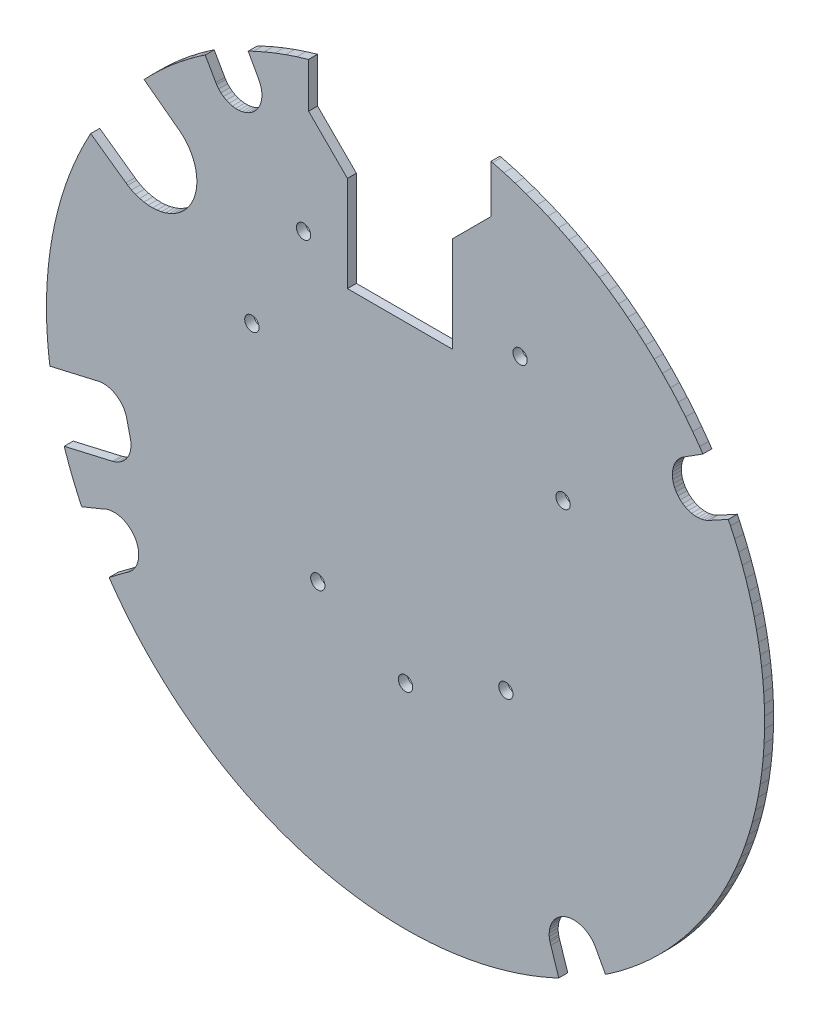
SolidWorks part; units mm, degrees
ref_plane "Płaszczyzna przednia" through (0, 0, 0) normal (0, 0, 1) x (1, 0, 0)
ref_plane "Płaszczyzna górna" through (0, 0, 0) normal (0, 1, 0) x (1, 0, 0)
ref_plane "Płaszczyzna prawa" through (0, 0, 0) normal (1, 0, 0) x (0, 0, -1)
sketch "Model" plane through (0, 0, 0) normal (0, 0, 1) x (1, 0, 0)
  line L0 (19.0436, 77.7128) -> (19.4019, 77.6294)
  line L1 (19.0436, 77.7128) -> (19.0437, 67.0537)
  line L2 (10.4176, 58.4277) -> (19.0437, 67.0537)
  line L3 (10.4176, 37.1511) -> (10.4176, 58.4277)
  line L4 (-12.9504, 37.1511) -> (10.4176, 37.1511)
  line L5 (-12.9504, 58.4177) -> (-12.9504, 37.1511)
  line L6 (-12.9603, 58.4177) -> (-12.9504, 58.4177)
  line L7 (-21.5964, 67.0537) -> (-12.9603, 58.4177)
  line L8 (-21.5964, 77.0457) -> (-21.5964, 67.0537)
  line L9 (-21.7211, 77.0127) -> (-21.5964, 77.0457)
  line L10 (-24.2112, 76.2665) -> (-21.7211, 77.0127)
  line L11 (-26.6758, 75.4398) -> (-24.2112, 76.2665)
  line L12 (-29.1122, 74.5335) -> (-26.6758, 75.4398)
  line L13 (-31.5179, 73.5485) -> (-29.1122, 74.5335)
  line L14 (-33.8903, 72.4859) -> (-31.5179, 73.5485)
  line L15 (-35.0587, 71.9164) -> (-33.8903, 72.4859)
  line L16 (-35.0587, 71.9164) -> (-32.6893, 67.604)
  line L17 (-32.6893, 67.604) -> (-32.532, 67.296)
  line L18 (-32.532, 67.296) -> (-32.2769, 66.6533)
  line L19 (-32.2769, 66.6533) -> (-32.1045, 65.9836)
  line L20 (-32.1045, 65.9836) -> (-32.0176, 65.2976)
  line L21 (-32.0176, 65.2976) -> (-32.0067, 64.9519)
  line L22 (-32.0185, 64.5922) -> (-32.0067, 64.9519)
  line L23 (-32.1126, 63.8788) -> (-32.0185, 64.5922)
  line L24 (-32.2991, 63.1839) -> (-32.1126, 63.8788)
  line L25 (-32.5747, 62.5193) -> (-32.2991, 63.1839)
  line L26 (-32.9349, 61.8965) -> (-32.5747, 62.5193)
  line L27 (-33.3734, 61.3261) -> (-32.9349, 61.8965)
  line L28 (-33.8827, 60.8178) -> (-33.3734, 61.3261)
  line L29 (-34.4541, 60.3805) -> (-33.8827, 60.8178)
  line L30 (-35.0777, 60.0216) -> (-34.4541, 60.3805)
  line L31 (-35.7428, 59.7473) -> (-35.0777, 60.0216)
  line L32 (-36.4381, 59.5623) -> (-35.7428, 59.7473)
  line L33 (-37.1516, 59.4698) -> (-36.4381, 59.5623)
  line L34 (-37.8711, 59.4713) -> (-37.1516, 59.4698)
  line L35 (-38.5843, 59.5668) -> (-37.8711, 59.4713)
  line L36 (-39.2788, 59.7547) -> (-38.5843, 59.5668)
  line L37 (-39.9428, 60.0317) -> (-39.2788, 59.7547)
  line L38 (-40.5649, 60.3932) -> (-39.9428, 60.0317)
  line L39 (-41.1344, 60.8328) -> (-40.5649, 60.3932)
  line L40 (-41.6416, 61.3432) -> (-41.1344, 60.8328)
  line L41 (-42.0777, 61.9154) -> (-41.6416, 61.3432)
  line L42 (-42.2668, 62.2217) -> (-42.0777, 61.9154)
  line L43 (-44.6488, 66.3807) -> (-42.2668, 62.2217)
  line L44 (-45.8412, 65.5873) -> (-44.6488, 66.3807)
  line L45 (-48.1485, 63.9127) -> (-45.8412, 65.5873)
  line L46 (-50.3947, 62.1569) -> (-48.1485, 63.9127)
  line L47 (-52.5769, 60.3223) -> (-50.3947, 62.1569)
  line L48 (-54.6923, 58.4111) -> (-52.5769, 60.3223)
  line L49 (-56.7384, 56.4257) -> (-54.6923, 58.4111)
  line L50 (-58.2639, 54.8361) -> (-56.7384, 56.4257)
  line L51 (-58.2639, 54.8361) -> (-50.5268, 49.0454)
  line L52 (-50.5268, 49.0454) -> (-50.1364, 48.7535)
  line L53 (-50.1364, 48.7535) -> (-49.416, 48.0964)
  line L54 (-49.416, 48.0964) -> (-48.7629, 47.3723)
  line L55 (-48.7629, 47.3723) -> (-48.1833, 46.5882)
  line L56 (-48.1833, 46.5882) -> (-47.6828, 45.7514)
  line L57 (-47.6828, 45.7514) -> (-47.2661, 44.8699)
  line L58 (-47.2661, 44.8699) -> (-46.937, 43.952)
  line L59 (-46.937, 43.952) -> (-46.6989, 43.0065)
  line L60 (-46.6989, 43.0065) -> (-46.5538, 42.0423)
  line L61 (-46.5538, 42.0423) -> (-46.5032, 41.0685)
  line L62 (-46.5476, 40.0945) -> (-46.5032, 41.0685)
  line L63 (-46.6865, 39.1294) -> (-46.5476, 40.0945)
  line L64 (-46.9186, 38.1823) -> (-46.6865, 39.1294)
  line L65 (-47.2418, 37.2624) -> (-46.9186, 38.1823)
  line L66 (-47.6529, 36.3782) -> (-47.2418, 37.2624)
  line L67 (-48.148, 35.5383) -> (-47.6529, 36.3782)
  line L68 (-48.7226, 34.7504) -> (-48.148, 35.5383)
  line L69 (-49.371, 34.0222) -> (-48.7226, 34.7504)
  line L70 (-50.0872, 33.3606) -> (-49.371, 34.0222)
  line L71 (-50.8644, 32.7717) -> (-50.0872, 33.3606)
  line L72 (-51.6951, 32.2612) -> (-50.8644, 32.7717)
  line L73 (-52.5716, 31.834) -> (-51.6951, 32.2612)
  line L74 (-53.4855, 31.494) -> (-52.5716, 31.834)
  line L75 (-54.4281, 31.2446) -> (-53.4855, 31.494)
  line L76 (-55.3905, 31.088) -> (-54.4281, 31.2446)
  line L77 (-56.3636, 31.0258) -> (-55.3905, 31.088)
  line L78 (-57.3381, 31.0586) -> (-56.3636, 31.0258)
  line L79 (-58.3048, 31.1859) -> (-57.3381, 31.0586)
  line L80 (-59.2545, 31.4068) -> (-58.3048, 31.1859)
  line L81 (-60.1783, 31.7189) -> (-59.2545, 31.4068)
  line L82 (-61.0673, 32.1195) -> (-60.1783, 31.7189)
  line L83 (-61.9131, 32.6046) -> (-61.0673, 32.1195)
  line L84 (-62.3104, 32.8871) -> (-61.9131, 32.6046)
  line L85 (-70.16, 38.4692) -> (-62.3104, 32.8871)
  line L86 (-70.3157, 38.1943) -> (-70.16, 38.4692)
  line L87 (-71.6317, 35.6653) -> (-70.3157, 38.1943)
  line L88 (-72.8567, 33.0909) -> (-71.6317, 35.6653)
  line L89 (-73.9893, 30.4746) -> (-72.8567, 33.0909)
  line L90 (-75.0279, 27.8195) -> (-73.9893, 30.4746)
  line L91 (-75.9713, 25.1292) -> (-75.0279, 27.8195)
  line L92 (-76.8182, 22.4069) -> (-75.9713, 25.1292)
  line L93 (-77.5677, 19.6563) -> (-76.8182, 22.4069)
  line L94 (-78.2186, 16.8806) -> (-77.5677, 19.6563)
  line L95 (-78.7703, 14.0836) -> (-78.2186, 16.8806)
  line L96 (-79.222, 11.2686) -> (-78.7703, 14.0836)
  line L97 (-79.5731, 8.4394) -> (-79.222, 11.2686)
  line L98 (-79.8233, 5.5994) -> (-79.5731, 8.4394)
  line L99 (-79.9721, 2.7524) -> (-79.8233, 5.5994)
  line L100 (-80.0194, -0.0982) -> (-79.9721, 2.7524)
  line L101 (-80.0194, -0.0982) -> (-79.9651, -2.9486)
  line L102 (-79.9651, -2.9486) -> (-79.8093, -5.7953)
  line L103 (-79.8093, -5.7953) -> (-79.5522, -8.6347)
  line L104 (-79.5522, -8.6347) -> (-79.256, -10.9739)
  line L105 (-79.256, -10.9739) -> (-68.5352, -8.4988)
  line L106 (-68.5352, -8.4988) -> (-68.1939, -8.42)
  line L107 (-68.1939, -8.42) -> (-67.4966, -8.3528)
  line L108 (-67.4966, -8.3528) -> (-66.7965, -8.3773)
  line L109 (-66.7965, -8.3773) -> (-66.1056, -8.4929)
  line L110 (-66.1056, -8.4929) -> (-65.4357, -8.6977)
  line L111 (-65.4357, -8.6977) -> (-64.7982, -8.9882)
  line L112 (-64.7982, -8.9882) -> (-64.2042, -9.3594)
  line L113 (-64.2042, -9.3594) -> (-63.6636, -9.805)
  line L114 (-63.6636, -9.805) -> (-63.1859, -10.3174)
  line L115 (-63.1859, -10.3174) -> (-62.7791, -10.8877)
  line L116 (-62.7791, -10.8877) -> (-62.4502, -11.5062)
  line L117 (-62.4502, -11.5062) -> (-62.2049, -12.1624)
  line L118 (-62.2049, -12.1624) -> (-62.1261, -12.5037)
  line L119 (-62.1261, -12.5037) -> (-61.3306, -15.949)
  line L120 (-61.3306, -15.949) -> (-61.2518, -16.2903)
  line L121 (-61.2518, -16.2903) -> (-61.1847, -16.9876)
  line L122 (-61.2092, -17.6877) -> (-61.1847, -16.9876)
  line L123 (-61.3248, -18.3787) -> (-61.2092, -17.6877)
  line L124 (-61.5296, -19.0486) -> (-61.3248, -18.3787)
  line L125 (-61.8201, -19.686) -> (-61.5296, -19.0486)
  line L126 (-62.1913, -20.2801) -> (-61.8201, -19.686)
  line L127 (-62.6369, -20.8206) -> (-62.1913, -20.2801)
  line L128 (-63.1492, -21.2984) -> (-62.6369, -20.8206)
  line L129 (-63.7196, -21.7052) -> (-63.1492, -21.2984)
  line L130 (-64.3381, -22.0341) -> (-63.7196, -21.7052)
  line L131 (-64.9942, -22.2794) -> (-64.3381, -22.0341)
  line L132 (-65.3355, -22.3582) -> (-64.9942, -22.2794)
  line L133 (-76.0604, -24.8342) -> (-65.3355, -22.3582)
  line L134 (-76.0604, -24.8342) -> (-75.9094, -25.3156)
  line L135 (-75.9094, -25.3156) -> (-74.9594, -28.0036)
  line L136 (-74.9594, -28.0036) -> (-73.9142, -30.6561)
  line L137 (-73.9142, -30.6561) -> (-72.7753, -33.2696)
  line L138 (-72.7753, -33.2696) -> (-72.1596, -34.5553)
  line L139 (-72.1596, -34.5553) -> (-67.6684, -32.7253)
  line L140 (-67.6684, -32.7253) -> (-67.3503, -32.558)
  line L141 (-67.3503, -32.558) -> (-66.6869, -32.2879)
  line L142 (-66.6869, -32.2879) -> (-65.9939, -32.1065)
  line L143 (-65.9939, -32.1065) -> (-65.2832, -32.0167)
  line L144 (-65.2832, -32.0167) -> (-64.5669, -32.0202)
  line L145 (-64.5669, -32.0202) -> (-63.8572, -32.1169)
  line L146 (-63.8572, -32.1169) -> (-63.166, -32.3051)
  line L147 (-63.166, -32.3051) -> (-62.5052, -32.5817)
  line L148 (-62.5052, -32.5817) -> (-61.886, -32.9419)
  line L149 (-61.886, -32.9419) -> (-61.319, -33.3796)
  line L150 (-61.319, -33.3796) -> (-60.8137, -33.8873)
  line L151 (-60.8137, -33.8873) -> (-60.3788, -34.4565)
  line L152 (-60.3788, -34.4565) -> (-60.0217, -35.0774)
  line L153 (-60.0217, -35.0774) -> (-59.7484, -35.7396)
  line L154 (-59.7484, -35.7396) -> (-59.5635, -36.4316)
  line L155 (-59.5635, -36.4316) -> (-59.4703, -37.1418)
  line L156 (-59.4703, -37.1418) -> (-59.4586, -37.5)
  line L157 (-59.4706, -37.8617) -> (-59.4586, -37.5)
  line L158 (-59.5656, -38.5787) -> (-59.4706, -37.8617)
  line L159 (-59.754, -39.277) -> (-59.5656, -38.5787)
  line L160 (-60.0325, -39.9445) -> (-59.754, -39.277)
  line L161 (-60.3964, -40.5697) -> (-60.0325, -39.9445)
  line L162 (-60.8392, -41.1416) -> (-60.3964, -40.5697)
  line L163 (-61.3533, -41.6504) -> (-60.8392, -41.1416)
  line L164 (-61.9297, -42.0872) -> (-61.3533, -41.6504)
  line L165 (-62.2383, -42.2762) -> (-61.9297, -42.0872)
  line L166 (-66.0586, -45.1369) -> (-62.2383, -42.2762)
  line L167 (-66.0586, -45.1369) -> (-65.2616, -46.3033)
  line L168 (-65.2616, -46.3033) -> (-63.5863, -48.5783)
  line L169 (-63.5863, -48.5783) -> (-61.8318, -50.7928)
  line L170 (-61.8318, -50.7928) -> (-60.0001, -52.9439)
  line L171 (-60.0001, -52.9439) -> (-58.0936, -55.0291)
  line L172 (-58.0936, -55.0291) -> (-56.1148, -57.0456)
  line L173 (-56.1148, -57.0456) -> (-54.0659, -58.9911)
  line L174 (-54.0659, -58.9911) -> (-51.9497, -60.863)
  line L175 (-51.9497, -60.863) -> (-49.7687, -62.659)
  line L176 (-49.7687, -62.659) -> (-47.5256, -64.3769)
  line L177 (-47.5256, -64.3769) -> (-45.2234, -66.0146)
  line L178 (-45.2234, -66.0146) -> (-42.8647, -67.5699)
  line L179 (-42.8647, -67.5699) -> (-40.4526, -69.041)
  line L180 (-40.4526, -69.041) -> (-37.99, -70.4261)
  line L181 (-37.99, -70.4261) -> (-35.4801, -71.7233)
  line L182 (-35.4801, -71.7233) -> (-32.926, -72.9311)
  line L183 (-32.926, -72.9311) -> (-30.3308, -74.0481)
  line L184 (-30.3308, -74.0481) -> (-27.6978, -75.0727)
  line L185 (-27.6978, -75.0727) -> (-25.0303, -76.0037)
  line L186 (-25.0303, -76.0037) -> (-22.3316, -76.8399)
  line L187 (-22.3316, -76.8399) -> (-19.605, -77.5804)
  line L188 (-19.605, -77.5804) -> (-16.854, -78.2241)
  line L189 (-16.854, -78.2241) -> (-14.082, -78.7704)
  line L190 (-14.082, -78.7704) -> (-11.2924, -79.2184)
  line L191 (-11.2924, -79.2184) -> (-8.4887, -79.5677)
  line L192 (-8.4887, -79.5677) -> (-5.6745, -79.8177)
  line L193 (-5.6745, -79.8177) -> (-2.8532, -79.9683)
  line L194 (-2.8532, -79.9683) -> (-0.0283, -80.0192)
  line L195 (-0.0283, -80.0192) -> (2.7966, -79.9703)
  line L196 (2.7966, -79.9703) -> (5.618, -79.8217)
  line L197 (5.618, -79.8217) -> (8.4324, -79.5737)
  line L198 (8.4324, -79.5737) -> (11.2363, -79.2264)
  line L199 (11.2363, -79.2264) -> (14.0262, -78.7803)
  line L200 (14.0262, -78.7803) -> (16.7986, -78.2361)
  line L201 (16.7986, -78.2361) -> (19.55, -77.5943)
  line L202 (19.55, -77.5943) -> (22.2771, -76.8557)
  line L203 (22.2771, -76.8557) -> (24.9765, -76.0214)
  line L204 (24.9765, -76.0214) -> (27.6446, -75.0923)
  line L205 (27.6446, -75.0923) -> (30.2784, -74.0695)
  line L206 (30.2784, -74.0695) -> (32.8743, -72.9544)
  line L207 (32.8743, -72.9544) -> (34.1518, -72.3514)
  line L208 (32.3764, -66.933) -> (34.1518, -72.3514)
  line L209 (32.2006, -66.3985) -> (32.3764, -66.933)
  line L210 (32.1226, -66.0744) -> (32.2006, -66.3985)
  line L211 (32.0263, -65.415) -> (32.1226, -66.0744)
  line L212 (32.0105, -64.7488) -> (32.0263, -65.415)
  line L213 (32.0105, -64.7488) -> (32.0755, -64.0856)
  line L214 (32.0755, -64.0856) -> (32.2203, -63.4352)
  line L215 (32.2203, -63.4352) -> (32.4428, -62.8071)
  line L216 (32.4428, -62.8071) -> (32.7397, -62.2105)
  line L217 (32.7397, -62.2105) -> (33.1067, -61.6543)
  line L218 (33.1067, -61.6543) -> (33.5383, -61.1466)
  line L219 (33.5383, -61.1466) -> (34.0282, -60.6949)
  line L220 (34.0282, -60.6949) -> (34.5692, -60.3059)
  line L221 (34.5692, -60.3059) -> (35.1534, -59.9852)
  line L222 (35.1534, -59.9852) -> (35.772, -59.7376)
  line L223 (35.772, -59.7376) -> (36.4161, -59.5667)
  line L224 (36.4161, -59.5667) -> (37.0762, -59.4751)
  line L225 (37.0762, -59.4751) -> (37.7424, -59.4641)
  line L226 (37.7424, -59.4641) -> (38.4052, -59.5338)
  line L227 (38.4052, -59.5338) -> (39.0545, -59.6833)
  line L228 (39.0545, -59.6833) -> (39.6811, -59.9102)
  line L229 (39.6811, -59.9102) -> (40.2755, -60.2114)
  line L230 (40.2755, -60.2114) -> (40.8291, -60.5824)
  line L231 (40.8291, -60.5824) -> (41.3337, -61.0176)
  line L232 (41.3337, -61.0176) -> (41.7818, -61.5107)
  line L233 (41.7818, -61.5107) -> (42.167, -62.0545)
  line L234 (42.167, -62.0545) -> (42.3342, -62.3429)
  line L235 (42.3342, -62.3429) -> (44.5493, -66.4474)
  line L236 (44.5493, -66.4474) -> (45.7221, -65.6698)
  line L237 (45.7221, -65.6698) -> (47.9923, -64.0295)
  line L238 (47.9923, -64.0295) -> (50.2037, -62.3107)
  line L239 (50.2037, -62.3107) -> (52.3536, -60.5156)
  line L240 (52.3536, -60.5156) -> (54.4394, -58.6463)
  line L241 (54.4394, -58.6463) -> (56.4584, -56.7052)
  line L242 (56.4584, -56.7052) -> (58.4083, -54.6947)
  line L243 (58.4083, -54.6947) -> (60.2867, -52.6171)
  line L244 (60.2867, -52.6171) -> (62.0911, -50.475)
  line L245 (62.0911, -50.475) -> (63.8195, -48.2711)
  line L246 (63.8195, -48.2711) -> (65.4698, -46.0081)
  line L247 (65.4698, -46.0081) -> (67.0398, -43.6887)
  line L248 (67.0398, -43.6887) -> (68.5277, -41.3158)
  line L249 (68.5277, -41.3158) -> (69.9316, -38.8923)
  line L250 (69.9316, -38.8923) -> (71.2498, -36.4211)
  line L251 (71.2498, -36.4211) -> (72.4808, -33.9053)
  line L252 (72.4808, -33.9053) -> (73.623, -31.348)
  line L253 (73.623, -31.348) -> (74.6749, -28.7523)
  line L254 (74.6749, -28.7523) -> (75.6354, -26.1213)
  line L255 (75.6354, -26.1213) -> (76.5032, -23.4583)
  line L256 (76.5032, -23.4583) -> (77.2773, -20.7666)
  line L257 (77.2773, -20.7666) -> (77.9567, -18.0495)
  line L258 (77.9567, -18.0495) -> (78.5407, -15.3102)
  line L259 (78.5407, -15.3102) -> (79.0283, -12.5522)
  line L260 (79.0283, -12.5522) -> (79.4192, -9.7788)
  line L261 (79.4192, -9.7788) -> (79.7128, -6.9934)
  line L262 (79.7128, -6.9934) -> (79.9087, -4.1995)
  line L263 (79.9087, -4.1995) -> (80.0067, -1.4004)
  line L264 (80.0067, 0) -> (80.0067, -1.4004)
  line L265 (80.0067, 0) -> (80.0067, 1.1336)
  line L266 (79.9425, 3.4) -> (80.0067, 1.1336)
  line L267 (79.8141, 5.6637) -> (79.9425, 3.4)
  line L268 (79.6215, 7.9228) -> (79.8141, 5.6637)
  line L269 (79.3651, 10.1755) -> (79.6215, 7.9228)
  line L270 (79.0449, 12.4201) -> (79.3651, 10.1755)
  line L271 (78.6613, 14.6547) -> (79.0449, 12.4201)
  line L272 (78.2145, 16.8775) -> (78.6613, 14.6547)
  line L273 (77.7049, 19.0868) -> (78.2145, 16.8775)
  line L274 (77.1329, 21.2808) -> (77.7049, 19.0868)
  line L275 (76.499, 23.4576) -> (77.1329, 21.2808)
  line L276 (75.8037, 25.6157) -> (76.499, 23.4576)
  line L277 (75.0475, 27.7531) -> (75.8037, 25.6157)
  line L278 (74.231, 29.8683) -> (75.0475, 27.7531)
  line L279 (73.355, 31.9595) -> (74.231, 29.8683)
  line L280 (72.42, 34.0251) -> (73.355, 31.9595)
  line L281 (71.9234, 35.0442) -> (72.42, 34.0251)
  line L282 (67.5882, 32.6807) -> (71.9234, 35.0442)
  line L283 (67.2673, 32.5185) -> (67.5882, 32.6807)
  line L284 (66.5971, 32.2589) -> (67.2673, 32.5185)
  line L285 (65.8987, 32.0889) -> (66.5971, 32.2589)
  line L286 (65.1841, 32.0116) -> (65.8987, 32.0889)
  line L287 (64.4655, 32.0283) -> (65.1841, 32.0116)
  line L288 (63.7552, 32.1387) -> (64.4655, 32.0283)
  line L289 (63.0655, 32.3408) -> (63.7552, 32.1387)
  line L290 (62.408, 32.6313) -> (63.0655, 32.3408)
  line L291 (61.7941, 33.0051) -> (62.408, 32.6313)
  line L292 (61.2342, 33.4559) -> (61.7941, 33.0051)
  line L293 (60.738, 33.9759) -> (61.2342, 33.4559)
  line L294 (60.314, 34.5563) -> (60.738, 33.9759)
  line L295 (59.9693, 35.187) -> (60.314, 34.5563)
  line L296 (59.71, 35.8574) -> (59.9693, 35.187)
  line L297 (59.5404, 36.5559) -> (59.71, 35.8574)
  line L298 (59.4634, 37.2705) -> (59.5404, 36.5559)
  line L299 (59.4634, 37.2705) -> (59.4804, 37.9891)
  line L300 (59.4804, 37.9891) -> (59.5911, 38.6993)
  line L301 (59.5911, 38.6993) -> (59.7936, 39.3889)
  line L302 (59.7936, 39.3889) -> (60.0844, 40.0463)
  line L303 (60.0844, 40.0463) -> (60.4585, 40.66)
  line L304 (60.4585, 40.66) -> (60.9096, 41.2196)
  line L305 (60.9096, 41.2196) -> (61.4299, 41.7156)
  line L306 (61.4299, 41.7156) -> (62.0104, 42.1394)
  line L307 (62.0104, 42.1394) -> (62.3202, 42.3219)
  line L308 (62.3202, 42.3219) -> (66.2604, 44.8277)
  line L309 (65.534, 45.9137) -> (66.2604, 44.8277)
  line L310 (64.008, 48.0182) -> (65.534, 45.9137)
  line L311 (62.4144, 50.072) -> (64.008, 48.0182)
  line L312 (60.755, 52.073) -> (62.4144, 50.072)
  line L313 (59.0315, 54.019) -> (60.755, 52.073)
  line L314 (57.2456, 55.908) -> (59.0315, 54.019)
  line L315 (55.3994, 57.738) -> (57.2456, 55.908)
  line L316 (53.4946, 59.5071) -> (55.3994, 57.738)
  line L317 (51.5334, 61.2133) -> (53.4946, 59.5071)
  line L318 (49.5179, 62.855) -> (51.5334, 61.2133)
  line L319 (47.45, 64.4303) -> (49.5179, 62.855)
  line L320 (45.3321, 65.9376) -> (47.45, 64.4303)
  line L321 (43.1663, 67.3753) -> (45.3321, 65.9376)
  line L322 (40.955, 68.7419) -> (43.1663, 67.3753)
  line L323 (38.7005, 70.036) -> (40.955, 68.7419)
  line L324 (36.4051, 71.2561) -> (38.7005, 70.036)
  line L325 (34.0713, 72.4011) -> (36.4051, 71.2561)
  line L326 (31.7015, 73.4696) -> (34.0713, 72.4011)
  line L327 (29.2983, 74.4606) -> (31.7015, 73.4696)
  line L328 (26.8641, 75.373) -> (29.2983, 74.4606)
  line L329 (24.4016, 76.2058) -> (26.8641, 75.373)
  line L330 (21.9133, 76.9582) -> (24.4016, 76.2058)
  line L331 (19.4019, 77.6294) -> (21.9133, 76.9582)
  circle A0 centre (54.7436, 37.2036) radius 0.55
  circle A1 centre (54.7437, 42.2836) radius 0.55
  circle A2 centre (54.7436, 39.7436) radius 0.55
  circle A3 centre (-42.5084, 0.296) radius 0.45
  circle A4 centre (-45.0484, 0.296) radius 0.45
  circle A5 centre (-43.7784, 0.296) radius 0.45
  circle A6 centre (-37.6913, 41.9936) radius 0.51
  circle A7 centre (-35.7314, 47.9937) radius 0.635
  circle A8 centre (-35.7314, 35.9936) radius 0.635
  circle A9 centre (-37.6913, 38.9937) radius 0.51
  circle A10 centre (-37.6913, 44.9936) radius 0.51
  circle A11 centre (-70.8843, 18.7637) radius 0.5
  circle A12 centre (-68.3443, 18.7637) radius 0.5
  circle A13 centre (-43.2714, 18.7886) radius 0.5
  circle A14 centre (-40.7314, 18.7886) radius 0.5
  circle A15 centre (-56.8443, 18.7637) radius 0.5
  circle A16 centre (-54.3043, 18.7637) radius 0.5
  circle A17 centre (-39.9663, -46.0063) radius 0.7
  circle A18 centre (-45.0464, -46.0063) radius 0.7
  circle A19 centre (-50.1264, -43.5063) radius 1.2
  circle A20 centre (-34.8863, -43.5063) radius 1.2
  circle A21 centre (-57.9123, -11.637) radius 0.0875
  circle A22 centre (-57.9998, -11.637) radius 0.0437
  circle A23 centre (-57.8248, -11.637) radius 0.0437
  circle A24 centre (-56.3123, -11.637) radius 0.0875
  circle A25 centre (-56.3998, -11.637) radius 0.0437
  circle A26 centre (-56.2248, -11.637) radius 0.0437
  circle A27 centre (-0.7564, -72.3564) radius 2.275
  circle A28 centre (-0.7564, -65.1563) radius 2.275
  circle A29 centre (72.7187, -2.7063) radius 2.275
  circle A30 centre (65.5186, -2.7063) radius 2.275
  circle A31 centre (9.9101, -35.1099) radius 0.45
  circle A32 centre (7.3701, -35.1099) radius 0.45
  circle A33 centre (8.6401, -35.1099) radius 0.45
  circle A34 centre (44.2637, 16.4937) radius 0.45
  circle A35 centre (41.7237, 16.4937) radius 0.45
  circle A36 centre (42.9937, 16.4937) radius 0.45
  circle A37 centre (47.9187, 12.5686) radius 0.0875
  circle A38 centre (47.8312, 12.5686) radius 0.0437
  circle A39 centre (48.0062, 12.5686) radius 0.0437
  circle A40 centre (49.5187, 12.5686) radius 0.0875
  circle A41 centre (49.4312, 12.5686) radius 0.0437
  circle A42 centre (49.6062, 12.5686) radius 0.0437
  circle A43 centre (34.9286, -38.2563) radius 0.51
  circle A44 centre (34.9286, -44.2563) radius 0.51
  circle A45 centre (32.9687, -47.2563) radius 0.635
  circle A46 centre (32.9687, -35.2563) radius 0.635
  circle A47 centre (34.9286, -41.2563) radius 0.51
  circle A48 centre (47.9937, 30.2437) radius 0.51
  circle A49 centre (47.9937, 42.2437) radius 0.51
  circle A50 centre (47.9937, 39.2437) radius 0.51
  circle A51 centre (47.9937, 45.2437) radius 0.51
  circle A52 centre (47.9937, 33.2436) radius 0.51
  circle A53 centre (47.9937, 36.2437) radius 0.51
  circle A54 centre (49.9537, 48.2437) radius 0.635
  circle A55 centre (49.9537, 27.2437) radius 0.635
  circle A56 centre (58.2437, 21.4937) radius 0.5
  circle A57 centre (63.3236, 21.4936) radius 0.5
  circle A58 centre (60.7837, 21.4936) radius 0.5
  circle A59 centre (65.8637, 21.4936) radius 0.5
  circle A60 centre (31.75, 3.048) radius 0.381
  circle A61 centre (31.75, 5.588) radius 0.381
  circle A62 centre (-11.5063, -69.7564) radius 0.4
  circle A63 centre (-11.5063, -64.7564) radius 0.4
  circle A64 centre (35.814, 15.494) radius 0.55
  circle A65 centre (35.814, 10.414) radius 0.55
  circle A66 centre (35.814, 12.954) radius 0.55
  circle A67 centre (35.814, 2.286) radius 0.55
  circle A68 centre (35.814, 4.826) radius 0.55
  circle A69 centre (35.814, 7.366) radius 0.55
  circle A70 centre (65.2436, -14.0063) radius 0.4
  circle A71 centre (60.2436, -14.0063) radius 0.4
  circle A72 centre (72.7436, 13.7437) radius 0.55
  circle A73 centre (72.7436, 11.2036) radius 0.55
  circle A74 centre (72.7436, 8.6636) radius 0.55
  circle A75 centre (26.801, 38.231) radius 0.381
  circle A76 centre (24.261, 38.231) radius 0.381
  circle A77 centre (21.086, 15.371) radius 0.381
  circle A78 centre (-21.459, 38.231) radius 0.381
  circle A79 centre (-23.999, 38.231) radius 0.381
  circle A80 centre (24.261, 25.531) radius 0.381
  circle A81 centre (25.531, 43.311) radius 1.5875
  circle A82 centre (-22.729, 43.311) radius 1.5875
  circle A83 centre (22.356, -22.729) radius 1.5875
  circle A84 centre (-19.554, -22.729) radius 1.5875
  circle A85 centre (-21.459, 35.691) radius 0.381
  circle A86 centre (-23.999, 35.691) radius 0.381
  circle A87 centre (-21.459, 33.151) radius 0.381
  circle A88 centre (-23.999, 33.151) radius 0.381
  circle A89 centre (-21.459, 28.071) radius 0.381
  circle A90 centre (-21.459, 25.531) radius 0.381
  circle A91 centre (-23.999, 25.531) radius 0.381
  circle A92 centre (-21.459, 22.991) radius 0.381
  circle A93 centre (-23.999, 22.991) radius 0.381
  circle A94 centre (-21.459, 20.451) radius 0.381
  circle A95 centre (-23.999, 20.451) radius 0.381
  circle A96 centre (-21.459, 17.911) radius 0.381
  circle A97 centre (-21.459, 15.371) radius 0.381
  circle A98 centre (-23.999, 15.371) radius 0.381
  circle A99 centre (-21.459, 12.831) radius 0.381
  circle A100 centre (-23.999, 12.831) radius 0.381
  circle A101 centre (-21.459, 10.291) radius 0.381
  circle A102 centre (-23.999, 10.291) radius 0.381
  circle A103 centre (-21.459, 7.751) radius 0.381
  circle A104 centre (-21.459, 5.211) radius 0.381
  circle A105 centre (-23.999, 5.211) radius 0.381
  circle A106 centre (-21.459, 2.671) radius 0.381
  circle A107 centre (-23.999, 2.671) radius 0.381
  circle A108 centre (-21.459, 0.131) radius 0.381
  circle A109 centre (-23.999, 0.131) radius 0.381
  circle A110 centre (-21.459, -2.409) radius 0.381
  circle A111 centre (-23.999, -2.409) radius 0.381
  circle A112 centre (-21.459, -4.949) radius 0.381
  circle A113 centre (-23.999, -4.949) radius 0.381
  circle A114 centre (-21.459, -7.489) radius 0.381
  circle A115 centre (-23.999, -7.489) radius 0.381
  circle A116 centre (-21.459, -10.029) radius 0.381
  circle A117 centre (-23.999, -10.029) radius 0.381
  circle A118 centre (-21.459, -12.569) radius 0.381
  circle A119 centre (-23.999, -12.569) radius 0.381
  circle A120 centre (-21.459, -15.109) radius 0.381
  circle A121 centre (-23.999, -15.109) radius 0.381
  circle A122 centre (-21.459, -17.649) radius 0.381
  circle A123 centre (-23.999, -17.649) radius 0.381
  circle A124 centre (26.801, 35.691) radius 0.381
  circle A125 centre (24.261, 35.691) radius 0.381
  circle A126 centre (24.261, 33.151) radius 0.381
  circle A127 centre (26.801, 30.611) radius 0.381
  circle A128 centre (24.261, 30.611) radius 0.381
  circle A129 centre (26.801, 28.071) radius 0.381
  circle A130 centre (24.261, 28.071) radius 0.381
  circle A131 centre (24.261, 22.991) radius 0.381
  circle A132 centre (26.801, 20.451) radius 0.381
  circle A133 centre (24.261, 20.451) radius 0.381
  circle A134 centre (26.801, 17.911) radius 0.381
  circle A135 centre (24.261, 17.911) radius 0.381
  circle A136 centre (26.801, 15.371) radius 0.381
  circle A137 centre (24.261, 15.371) radius 0.381
  circle A138 centre (26.801, 10.291) radius 0.381
  circle A139 centre (26.801, 7.751) radius 0.381
  circle A140 centre (26.801, 5.211) radius 0.381
  circle A141 centre (24.261, 5.211) radius 0.381
  circle A142 centre (26.801, 2.671) radius 0.381
  circle A143 centre (24.261, 2.671) radius 0.381
  circle A144 centre (26.801, 0.131) radius 0.381
  circle A145 centre (24.261, 0.131) radius 0.381
  circle A146 centre (26.801, -2.409) radius 0.381
  circle A147 centre (24.261, -2.409) radius 0.381
  circle A148 centre (26.801, -4.949) radius 0.381
  circle A149 centre (24.261, -4.949) radius 0.381
  circle A150 centre (26.801, -7.489) radius 0.381
  circle A151 centre (24.261, -7.489) radius 0.381
  circle A152 centre (26.801, -10.029) radius 0.381
  circle A153 centre (24.261, -10.029) radius 0.381
  circle A154 centre (26.801, -12.569) radius 0.381
  circle A155 centre (24.261, -12.569) radius 0.381
  circle A156 centre (26.801, -15.109) radius 0.381
  circle A157 centre (24.261, -15.109) radius 0.381
  circle A158 centre (26.801, -17.649) radius 0.381
  circle A159 centre (24.261, -17.649) radius 0.381
  circle A160 centre (21.086, 12.831) radius 0.381
  circle A161 centre (21.086, 10.291) radius 0.381
  circle A162 centre (21.086, 2.671) radius 0.381
  circle A163 centre (-23.999, 28.071) radius 0.381
  circle A164 centre (-23.999, 17.911) radius 0.381
  circle A165 centre (-21.459, 30.611) radius 0.381
  circle A166 centre (24.261, 7.751) radius 0.381
  circle A167 centre (26.801, 25.531) radius 0.381
  circle A168 centre (-23.999, 30.611) radius 0.381
  circle A169 centre (26.801, 22.991) radius 0.381
  circle A170 centre (24.261, 12.831) radius 0.381
  circle A171 centre (26.801, 12.831) radius 0.381
  circle A172 centre (26.801, 33.151) radius 0.381
  circle A173 centre (-23.999, 7.751) radius 0.381
  circle A174 centre (21.086, 7.751) radius 0.381
  circle A175 centre (21.086, 5.211) radius 0.381
  circle A176 centre (24.261, 10.291) radius 0.381
  circle A179 centre (19.0436, 77.7128) radius 0.25
  circle A182 centre (19.0437, 67.0537) radius 0.25
  circle A184 centre (10.4176, 58.4277) radius 0.25
  circle A186 centre (10.4176, 37.1511) radius 0.25
  circle A188 centre (-12.9504, 37.1511) radius 0.25
  circle A190 centre (-12.9504, 58.4177) radius 0.25
  circle A192 centre (-12.9603, 58.4177) radius 0.25
  circle A194 centre (-21.5964, 67.0537) radius 0.25
  circle A196 centre (-21.5964, 77.0457) radius 0.25
  circle A198 centre (-21.7211, 77.0127) radius 0.25
  circle A200 centre (-24.2112, 76.2665) radius 0.25
  circle A202 centre (-26.6758, 75.4398) radius 0.25
  circle A204 centre (-29.1122, 74.5335) radius 0.25
  circle A206 centre (-31.5179, 73.5485) radius 0.25
  circle A208 centre (-33.8903, 72.4859) radius 0.25
  circle A209 centre (-35.0587, 71.9164) radius 0.25
  circle A211 centre (-32.6893, 67.604) radius 0.25
  circle A213 centre (-32.532, 67.296) radius 0.25
  circle A215 centre (-32.2769, 66.6533) radius 0.25
  circle A217 centre (-32.1045, 65.9836) radius 0.25
  circle A219 centre (-32.0176, 65.2976) radius 0.25
  circle A222 centre (-32.0067, 64.9519) radius 0.25
  circle A224 centre (-32.0185, 64.5922) radius 0.25
  circle A226 centre (-32.1126, 63.8788) radius 0.25
  circle A228 centre (-32.2991, 63.1839) radius 0.25
  circle A230 centre (-32.5747, 62.5193) radius 0.25
  circle A232 centre (-32.9349, 61.8965) radius 0.25
  circle A234 centre (-33.3734, 61.3261) radius 0.25
  circle A236 centre (-33.8827, 60.8178) radius 0.25
  circle A238 centre (-34.4541, 60.3805) radius 0.25
  circle A240 centre (-35.0777, 60.0216) radius 0.25
  circle A242 centre (-35.7428, 59.7473) radius 0.25
  circle A244 centre (-36.4381, 59.5623) radius 0.25
  circle A246 centre (-37.1516, 59.4698) radius 0.25
  circle A248 centre (-37.8711, 59.4713) radius 0.25
  circle A250 centre (-38.5843, 59.5668) radius 0.25
  circle A252 centre (-39.2788, 59.7547) radius 0.25
  circle A254 centre (-39.9428, 60.0317) radius 0.25
  circle A256 centre (-40.5649, 60.3932) radius 0.25
  circle A258 centre (-41.1344, 60.8328) radius 0.25
  circle A260 centre (-41.6416, 61.3432) radius 0.25
  circle A262 centre (-42.0777, 61.9154) radius 0.25
  circle A264 centre (-42.2668, 62.2217) radius 0.25
  circle A266 centre (-44.6488, 66.3807) radius 0.25
  circle A268 centre (-45.8412, 65.5873) radius 0.25
  circle A270 centre (-48.1485, 63.9127) radius 0.25
  circle A272 centre (-50.3947, 62.1569) radius 0.25
  circle A274 centre (-52.5769, 60.3223) radius 0.25
  circle A276 centre (-54.6923, 58.4111) radius 0.25
  circle A278 centre (-56.7384, 56.4257) radius 0.25
  circle A279 centre (-58.2639, 54.8361) radius 0.25
  circle A281 centre (-50.5268, 49.0454) radius 0.25
  circle A283 centre (-50.1364, 48.7535) radius 0.25
  circle A285 centre (-49.416, 48.0964) radius 0.25
  circle A287 centre (-48.7629, 47.3723) radius 0.25
  circle A289 centre (-48.1833, 46.5882) radius 0.25
  circle A291 centre (-47.6828, 45.7514) radius 0.25
  circle A293 centre (-47.2661, 44.8699) radius 0.25
  circle A295 centre (-46.937, 43.952) radius 0.25
  circle A297 centre (-46.6989, 43.0065) radius 0.25
  circle A299 centre (-46.5538, 42.0423) radius 0.25
  circle A302 centre (-46.5032, 41.0685) radius 0.25
  circle A304 centre (-46.5476, 40.0945) radius 0.25
  circle A306 centre (-46.6865, 39.1294) radius 0.25
  circle A308 centre (-46.9186, 38.1823) radius 0.25
  circle A310 centre (-47.2418, 37.2624) radius 0.25
  circle A312 centre (-47.6529, 36.3782) radius 0.25
  circle A314 centre (-48.148, 35.5383) radius 0.25
  circle A316 centre (-48.7226, 34.7504) radius 0.25
  circle A318 centre (-49.371, 34.0222) radius 0.25
  circle A320 centre (-50.0872, 33.3606) radius 0.25
  circle A322 centre (-50.8644, 32.7717) radius 0.25
  circle A324 centre (-51.6951, 32.2612) radius 0.25
  circle A326 centre (-52.5716, 31.834) radius 0.25
  circle A328 centre (-53.4855, 31.494) radius 0.25
  circle A330 centre (-54.4281, 31.2446) radius 0.25
  circle A332 centre (-55.3905, 31.088) radius 0.25
  circle A334 centre (-56.3636, 31.0258) radius 0.25
  circle A336 centre (-57.3381, 31.0586) radius 0.25
  circle A338 centre (-58.3048, 31.1859) radius 0.25
  circle A340 centre (-59.2545, 31.4068) radius 0.25
  circle A342 centre (-60.1783, 31.7189) radius 0.25
  circle A344 centre (-61.0673, 32.1195) radius 0.25
  circle A346 centre (-61.9131, 32.6046) radius 0.25
  circle A350 centre (-62.3104, 32.8871) radius 0.25
  circle A352 centre (-70.16, 38.4692) radius 0.25
  circle A354 centre (-70.3157, 38.1943) radius 0.25
  circle A356 centre (-71.6317, 35.6653) radius 0.25
  circle A358 centre (-72.8567, 33.0909) radius 0.25
  circle A360 centre (-73.9893, 30.4746) radius 0.25
  circle A362 centre (-75.0279, 27.8195) radius 0.25
  circle A364 centre (-75.9713, 25.1292) radius 0.25
  circle A366 centre (-76.8182, 22.4069) radius 0.25
  circle A368 centre (-77.5677, 19.6563) radius 0.25
  circle A370 centre (-78.2186, 16.8806) radius 0.25
  circle A372 centre (-78.7703, 14.0836) radius 0.25
  circle A374 centre (-79.222, 11.2686) radius 0.25
  circle A376 centre (-79.5731, 8.4394) radius 0.25
  circle A378 centre (-79.8233, 5.5994) radius 0.25
  circle A380 centre (-79.9721, 2.7524) radius 0.25
  circle A381 centre (-80.0194, -0.0982) radius 0.25
  circle A383 centre (-79.9651, -2.9486) radius 0.25
  circle A385 centre (-79.8093, -5.7953) radius 0.25
  circle A387 centre (-79.5522, -8.6347) radius 0.25
  circle A389 centre (-79.256, -10.9739) radius 0.25
  circle A391 centre (-68.5352, -8.4988) radius 0.25
  circle A393 centre (-68.1939, -8.42) radius 0.25
  circle A395 centre (-67.4966, -8.3528) radius 0.25
  circle A397 centre (-66.7965, -8.3773) radius 0.25
  circle A399 centre (-66.1056, -8.4929) radius 0.25
  circle A401 centre (-65.4357, -8.6977) radius 0.25
  circle A403 centre (-64.7982, -8.9882) radius 0.25
  circle A405 centre (-64.2042, -9.3594) radius 0.25
  circle A407 centre (-63.6636, -9.805) radius 0.25
  circle A409 centre (-63.1859, -10.3174) radius 0.25
  circle A411 centre (-62.7791, -10.8877) radius 0.25
  circle A413 centre (-62.4502, -11.5062) radius 0.25
  circle A415 centre (-62.2049, -12.1624) radius 0.25
  circle A419 centre (-62.1261, -12.5037) radius 0.25
  circle A421 centre (-61.3306, -15.949) radius 0.25
  circle A423 centre (-61.2518, -16.2903) radius 0.25
  circle A426 centre (-61.1847, -16.9876) radius 0.25
  circle A428 centre (-61.2092, -17.6877) radius 0.25
  circle A430 centre (-61.3248, -18.3787) radius 0.25
  circle A432 centre (-61.5296, -19.0486) radius 0.25
  circle A434 centre (-61.8201, -19.686) radius 0.25
  circle A436 centre (-62.1913, -20.2801) radius 0.25
  circle A438 centre (-62.6369, -20.8206) radius 0.25
  circle A440 centre (-63.1492, -21.2984) radius 0.25
  circle A442 centre (-63.7196, -21.7052) radius 0.25
  circle A444 centre (-64.3381, -22.0341) radius 0.25
  circle A446 centre (-64.9942, -22.2794) radius 0.25
  circle A450 centre (-65.3355, -22.3582) radius 0.25
  circle A451 centre (-76.0604, -24.8342) radius 0.25
  circle A453 centre (-75.9094, -25.3156) radius 0.25
  circle A455 centre (-74.9594, -28.0036) radius 0.25
  circle A457 centre (-73.9142, -30.6561) radius 0.25
  circle A459 centre (-72.7753, -33.2696) radius 0.25
  circle A461 centre (-72.1596, -34.5553) radius 0.25
  circle A463 centre (-67.6684, -32.7253) radius 0.25
  circle A465 centre (-67.3503, -32.558) radius 0.25
  circle A467 centre (-66.6869, -32.2879) radius 0.25
  circle A469 centre (-65.9939, -32.1065) radius 0.25
  circle A471 centre (-65.2832, -32.0167) radius 0.25
  circle A473 centre (-64.5669, -32.0202) radius 0.25
  circle A475 centre (-63.8572, -32.1169) radius 0.25
  circle A477 centre (-63.166, -32.3051) radius 0.25
  circle A479 centre (-62.5052, -32.5817) radius 0.25
  circle A481 centre (-61.886, -32.9419) radius 0.25
  circle A483 centre (-61.319, -33.3796) radius 0.25
  circle A485 centre (-60.8137, -33.8873) radius 0.25
  circle A487 centre (-60.3788, -34.4565) radius 0.25
  circle A489 centre (-60.0217, -35.0774) radius 0.25
  circle A491 centre (-59.7484, -35.7396) radius 0.25
  circle A493 centre (-59.5635, -36.4316) radius 0.25
  circle A495 centre (-59.4703, -37.1418) radius 0.25
  circle A498 centre (-59.4586, -37.5) radius 0.25
  circle A500 centre (-59.4706, -37.8617) radius 0.25
  circle A502 centre (-59.5656, -38.5787) radius 0.25
  circle A504 centre (-59.754, -39.277) radius 0.25
  circle A506 centre (-60.0325, -39.9445) radius 0.25
  circle A508 centre (-60.3964, -40.5697) radius 0.25
  circle A510 centre (-60.8392, -41.1416) radius 0.25
  circle A512 centre (-61.3533, -41.6504) radius 0.25
  circle A514 centre (-61.9297, -42.0872) radius 0.25
  circle A516 centre (-62.2383, -42.2762) radius 0.25
  circle A517 centre (-66.0586, -45.1369) radius 0.25
  circle A519 centre (-65.2616, -46.3033) radius 0.25
  circle A521 centre (-63.5863, -48.5783) radius 0.25
  circle A523 centre (-61.8318, -50.7928) radius 0.25
  circle A525 centre (-60.0001, -52.9439) radius 0.25
  circle A527 centre (-58.0936, -55.0291) radius 0.25
  circle A529 centre (-56.1148, -57.0456) radius 0.25
  circle A531 centre (-54.0659, -58.9911) radius 0.25
  circle A533 centre (-51.9497, -60.863) radius 0.25
  circle A535 centre (-49.7687, -62.659) radius 0.25
  circle A537 centre (-47.5256, -64.3769) radius 0.25
  circle A539 centre (-45.2234, -66.0146) radius 0.25
  circle A541 centre (-42.8647, -67.5699) radius 0.25
  circle A543 centre (-40.4526, -69.041) radius 0.25
  circle A545 centre (-37.99, -70.4261) radius 0.25
  circle A547 centre (-35.4801, -71.7233) radius 0.25
  circle A549 centre (-32.926, -72.9311) radius 0.25
  circle A551 centre (-30.3308, -74.0481) radius 0.25
  circle A553 centre (-27.6978, -75.0727) radius 0.25
  circle A555 centre (-25.0303, -76.0037) radius 0.25
  circle A557 centre (-22.3316, -76.8399) radius 0.25
  circle A559 centre (-19.605, -77.5804) radius 0.25
  circle A561 centre (-16.854, -78.2241) radius 0.25
  circle A563 centre (-14.082, -78.7704) radius 0.25
  circle A565 centre (-11.2924, -79.2184) radius 0.25
  circle A567 centre (-8.4887, -79.5677) radius 0.25
  circle A569 centre (-5.6745, -79.8177) radius 0.25
  circle A571 centre (-2.8532, -79.9683) radius 0.25
  circle A573 centre (-0.0283, -80.0192) radius 0.25
  circle A575 centre (2.7966, -79.9703) radius 0.25
  circle A577 centre (5.618, -79.8217) radius 0.25
  circle A579 centre (8.4324, -79.5737) radius 0.25
  circle A581 centre (11.2363, -79.2264) radius 0.25
  circle A583 centre (14.0262, -78.7803) radius 0.25
  circle A585 centre (16.7986, -78.2361) radius 0.25
  circle A587 centre (19.55, -77.5943) radius 0.25
  circle A589 centre (22.2771, -76.8557) radius 0.25
  circle A591 centre (24.9765, -76.0214) radius 0.25
  circle A593 centre (27.6446, -75.0923) radius 0.25
  circle A595 centre (30.2784, -74.0695) radius 0.25
  circle A597 centre (32.8743, -72.9544) radius 0.25
  circle A600 centre (34.1518, -72.3514) radius 0.25
  circle A602 centre (32.3764, -66.933) radius 0.25
  circle A604 centre (32.2006, -66.3985) radius 0.25
  circle A606 centre (32.1226, -66.0744) radius 0.25
  circle A608 centre (32.0263, -65.415) radius 0.25
  circle A609 centre (32.0105, -64.7488) radius 0.25
  circle A611 centre (32.0755, -64.0856) radius 0.25
  circle A613 centre (32.2203, -63.4352) radius 0.25
  circle A615 centre (32.4428, -62.8071) radius 0.25
  circle A617 centre (32.7397, -62.2105) radius 0.25
  circle A619 centre (33.1067, -61.6543) radius 0.25
  circle A621 centre (33.5383, -61.1466) radius 0.25
  circle A623 centre (34.0282, -60.6949) radius 0.25
  circle A625 centre (34.5692, -60.3059) radius 0.25
  circle A627 centre (35.1534, -59.9852) radius 0.25
  circle A629 centre (35.772, -59.7376) radius 0.25
  circle A631 centre (36.4161, -59.5667) radius 0.25
  circle A633 centre (37.0762, -59.4751) radius 0.25
  circle A635 centre (37.7424, -59.4641) radius 0.25
  circle A637 centre (38.4052, -59.5338) radius 0.25
  circle A639 centre (39.0545, -59.6833) radius 0.25
  circle A641 centre (39.6811, -59.9102) radius 0.25
  circle A643 centre (40.2755, -60.2114) radius 0.25
  circle A645 centre (40.8291, -60.5824) radius 0.25
  circle A647 centre (41.3337, -61.0176) radius 0.25
  circle A649 centre (41.7818, -61.5107) radius 0.25
  circle A651 centre (42.167, -62.0545) radius 0.25
  circle A653 centre (42.3342, -62.3429) radius 0.25
  circle A655 centre (44.5493, -66.4474) radius 0.25
  circle A657 centre (45.7221, -65.6698) radius 0.25
  circle A659 centre (47.9923, -64.0295) radius 0.25
  circle A661 centre (50.2037, -62.3107) radius 0.25
  circle A663 centre (52.3536, -60.5156) radius 0.25
  circle A665 centre (54.4394, -58.6463) radius 0.25
  circle A667 centre (56.4584, -56.7052) radius 0.25
  circle A669 centre (58.4083, -54.6947) radius 0.25
  circle A671 centre (60.2867, -52.6171) radius 0.25
  circle A673 centre (62.0911, -50.475) radius 0.25
  circle A675 centre (63.8195, -48.2711) radius 0.25
  circle A677 centre (65.4698, -46.0081) radius 0.25
  circle A679 centre (67.0398, -43.6887) radius 0.25
  circle A681 centre (68.5277, -41.3158) radius 0.25
  circle A683 centre (69.9316, -38.8923) radius 0.25
  circle A685 centre (71.2498, -36.4211) radius 0.25
  circle A687 centre (72.4808, -33.9053) radius 0.25
  circle A689 centre (73.623, -31.348) radius 0.25
  circle A691 centre (74.6749, -28.7523) radius 0.25
  circle A693 centre (75.6354, -26.1213) radius 0.25
  circle A695 centre (76.5032, -23.4583) radius 0.25
  circle A697 centre (77.2773, -20.7666) radius 0.25
  circle A699 centre (77.9567, -18.0495) radius 0.25
  circle A701 centre (78.5407, -15.3102) radius 0.25
  circle A703 centre (79.0283, -12.5522) radius 0.25
  circle A705 centre (79.4192, -9.7788) radius 0.25
  circle A707 centre (79.7128, -6.9934) radius 0.25
  circle A709 centre (79.9087, -4.1995) radius 0.25
  circle A712 centre (80.0067, -1.4004) radius 0.25
  circle A713 centre (80.0067, 0) radius 0.25
  circle A716 centre (80.0067, 1.1336) radius 0.25
  circle A718 centre (79.9425, 3.4) radius 0.25
  circle A720 centre (79.8141, 5.6637) radius 0.25
  circle A722 centre (79.6215, 7.9228) radius 0.25
  circle A724 centre (79.3651, 10.1755) radius 0.25
  circle A726 centre (79.0449, 12.4201) radius 0.25
  circle A728 centre (78.6613, 14.6547) radius 0.25
  circle A730 centre (78.2145, 16.8775) radius 0.25
  circle A732 centre (77.7049, 19.0868) radius 0.25
  circle A734 centre (77.1329, 21.2808) radius 0.25
  circle A736 centre (76.499, 23.4576) radius 0.25
  circle A738 centre (75.8037, 25.6157) radius 0.25
  circle A740 centre (75.0475, 27.7531) radius 0.25
  circle A742 centre (74.231, 29.8683) radius 0.25
  circle A744 centre (73.355, 31.9595) radius 0.25
  circle A746 centre (72.42, 34.0251) radius 0.25
  circle A748 centre (71.9234, 35.0442) radius 0.25
  circle A750 centre (67.5882, 32.6807) radius 0.25
  circle A752 centre (67.2673, 32.5185) radius 0.25
  circle A754 centre (66.5971, 32.2589) radius 0.25
  circle A756 centre (65.8987, 32.0889) radius 0.25
  circle A758 centre (65.1841, 32.0116) radius 0.25
  circle A760 centre (64.4655, 32.0283) radius 0.25
  circle A762 centre (63.7552, 32.1387) radius 0.25
  circle A764 centre (63.0655, 32.3408) radius 0.25
  circle A766 centre (62.408, 32.6313) radius 0.25
  circle A768 centre (61.7941, 33.0051) radius 0.25
  circle A770 centre (61.2342, 33.4559) radius 0.25
  circle A772 centre (60.738, 33.9759) radius 0.25
  circle A774 centre (60.314, 34.5563) radius 0.25
  circle A776 centre (59.9693, 35.187) radius 0.25
  circle A778 centre (59.71, 35.8574) radius 0.25
  circle A780 centre (59.5404, 36.5559) radius 0.25
  circle A781 centre (59.4634, 37.2705) radius 0.25
  circle A783 centre (59.4804, 37.9891) radius 0.25
  circle A785 centre (59.5911, 38.6993) radius 0.25
  circle A787 centre (59.7936, 39.3889) radius 0.25
  circle A789 centre (60.0844, 40.0463) radius 0.25
  circle A791 centre (60.4585, 40.66) radius 0.25
  circle A793 centre (60.9096, 41.2196) radius 0.25
  circle A795 centre (61.4299, 41.7156) radius 0.25
  circle A797 centre (62.0104, 42.1394) radius 0.25
  circle A799 centre (62.3202, 42.3219) radius 0.25
  circle A802 centre (66.2604, 44.8277) radius 0.25
  circle A804 centre (65.534, 45.9137) radius 0.25
  circle A806 centre (64.008, 48.0182) radius 0.25
  circle A808 centre (62.4144, 50.072) radius 0.25
  circle A810 centre (60.755, 52.073) radius 0.25
  circle A812 centre (59.0315, 54.019) radius 0.25
  circle A814 centre (57.2456, 55.908) radius 0.25
  circle A816 centre (55.3994, 57.738) radius 0.25
  circle A818 centre (53.4946, 59.5071) radius 0.25
  circle A820 centre (51.5334, 61.2133) radius 0.25
  circle A822 centre (49.5179, 62.855) radius 0.25
  circle A824 centre (47.45, 64.4303) radius 0.25
  circle A826 centre (45.3321, 65.9376) radius 0.25
  circle A828 centre (43.1663, 67.3753) radius 0.25
  circle A830 centre (40.955, 68.7419) radius 0.25
  circle A832 centre (38.7005, 70.036) radius 0.25
  circle A834 centre (36.4051, 71.2561) radius 0.25
  circle A836 centre (34.0713, 72.4011) radius 0.25
  circle A838 centre (31.7015, 73.4696) radius 0.25
  circle A840 centre (29.2983, 74.4606) radius 0.25
  circle A842 centre (26.8641, 75.373) radius 0.25
  circle A844 centre (24.4016, 76.2058) radius 0.25
  circle A845 centre (19.4019, 77.6294) radius 0.25
  circle A846 centre (21.9133, 76.9582) radius 0.25
  circle A847 centre (35.1087, 20.27) radius 1.6
  circle A848 centre (0, -32.54) radius 1.6
  circle A849 centre (-34.2427, 19.77) radius 1.6
extrude "Boss-Extrude1" add sketch "Model" along normal blind 2 contours L85 L84 L83 L82 L81 L80 L79 L78 L77 L76 L75 L74 L73 L72 L71 L70 L69 L68 L67 L66 L65 L64 L63 L62 L61 L60 L59 L58 L57 L56 L55 L54 L53 L52 L51 L50 L49 L48 L47 L46 L45 L44 L43 L42 L41 L40 L39 L38 L37 L36 L35 L34 L33 L32 L31 L30 L29 L28 L27 L26 L25 L24 L23 L22 L21 L20 L19 L18 L17 L16 L15 L14 L13 L12 L11 L10 L9 L8 L7 L6 L5 L4 L3 L2 L1 L0 L331 L330 L329 L328 L327 L326 L325 L324 L323 L322 L321 L320 L319 L318 L317 L316 L315 L314 L313 L312 L311 L310 L309 L308 L307 L306 L305 L304 L303 L302 L301 L300 L299 L298 L297 L296 L295 L294 L293 L292 L291 L290 L289 L288 L287 L286 L285 L284 L283 L282 L281 L280 L279 L278 L277 L276 L275 L274 L273 L272 L271 L270 L269 L268 L267 L266 L265 L264 L263 L262 L261 L260 L259 L258 L257 L256 L255 L254 L253 L252 L251 L250 L249 L248 L247 L246 L245 L244 L243 L242 L241 L240 L239 L238 L237 L236 L235 L234 L233 L232 L231 L230 L229 L228 L227 L226 L225 L224 L223 L222 L221 L220 L219 L218 L217 L216 L215 L214 L213 L212 L211 L210 L209 L208 L207 L206 L205 L204 L203 L202 L201 L200 L199 L198 L197 L196 L195 L194 L193 L192 L191 L190 L189 L188 L187 L186 L185 L184 L183 L182 L181 L180 L179 L178 L177 L176 L175 L174 L173 L172 L171 L170 L169 L168 L167 L166 L165 L164 L163 L162 L161 L160 L159 L158 L157 L156 L155 L154 L153 L152 L151 L150 L149 L148 L147 L146 L145 L144 L143 L142 L141 L140 L139 L138 L137 L136 L135 L134 L133 L132 L131 L130 L129 L128 L127 L126 L125 L124 L123 L122 L121 L120 L119 L118 L117 L116 L115 L114 L113 L112 L111 L110 L109 L108 L107 L106 L105 L104 L103 L102 L101 L100 L99 L98 L97 L96 L95 L94 L93 L92 L91 L90 L89 L88 L87 L86 | A848 | A83 | A847 | A81 | A82 | A849 | A84
sketch "Sketch2" plane through (0, 0, 2) normal (0, 0, 1) x (1, 0, 0)
  line L0 (0, -32.54) -> (0, 0) construction
  line L1 (-34.2427, 19.77) -> (0, 0) construction
  line L2 (0, 0) -> (35.1087, 20.27) construction
  line L3 (-22.729, 43.311) -> (25.531, 43.311)
  line L4 (-22.729, 43.311) -> (-22.729, -22.689)
  line L5 (25.531, 43.311) -> (25.531, -22.689)
  line L6 (-22.729, -22.689) -> (25.531, -22.689)
  circle A0 centre (25.531, 43.311) radius 1.5875 construction
  circle A1 centre (-22.729, 43.311) radius 1.5875 construction
  circle A2 centre (25.531, 43.311) radius 1.5875
  circle A3 centre (-22.729, 43.311) radius 1.5875
  circle A4 centre (22.356, -22.729) radius 1.5875 construction
  circle A5 centre (-19.554, -22.729) radius 1.5875 construction
  circle A6 centre (22.356, -22.729) radius 1.5875
  circle A7 centre (-19.554, -22.729) radius 1.5875
  dimension "D1" = 120
  dimension "D2" = 39.54
  dimension "D3" = 40.54
  dimension "D4" = 32.54
  dimension "D5" = 66
